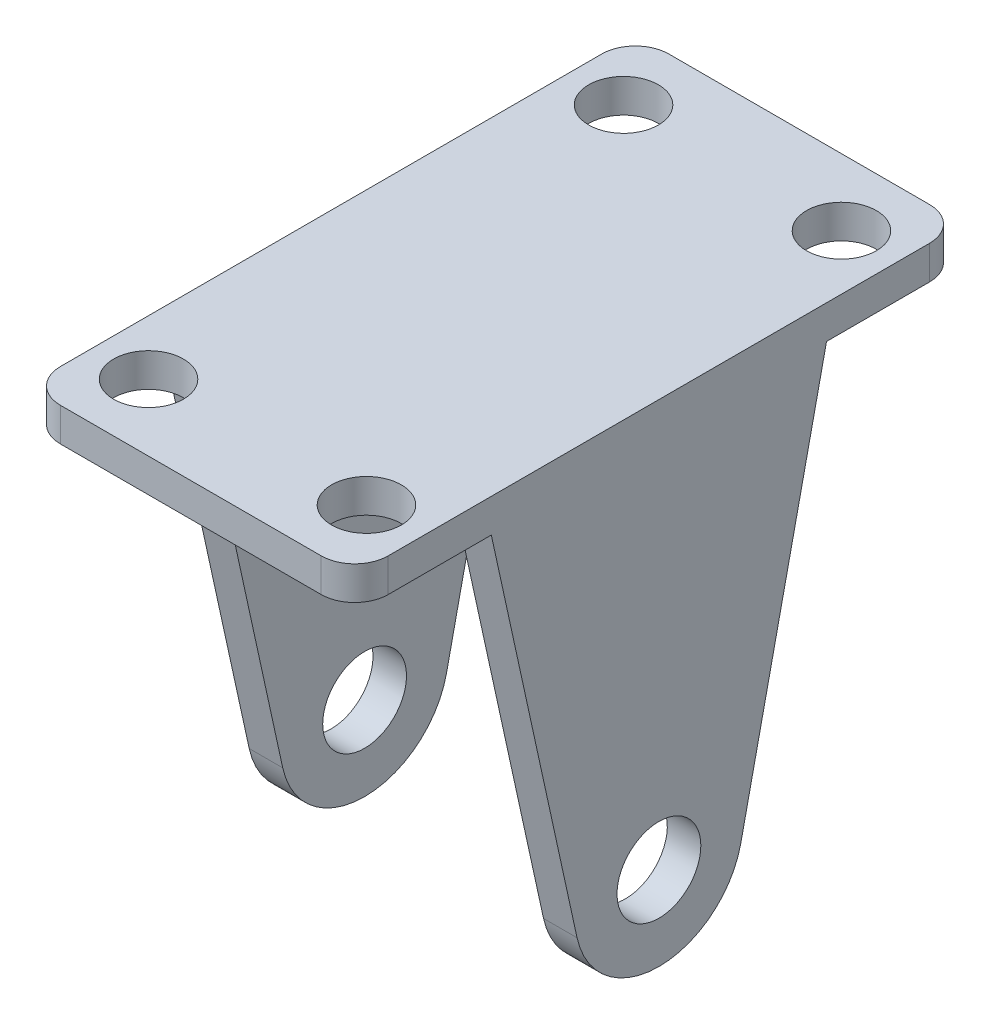
SolidWorks part; units mm, degrees
material "AISI 304"
ref_plane "Front Plane" through (0, 0, 0) normal (0, 0, 1) x (1, 0, 0)
ref_plane "Top Plane" through (0, 0, 0) normal (0, 1, 0) x (1, 0, 0)
ref_plane "Right Plane" through (0, 0, 0) normal (1, 0, 0) x (0, 0, -1)
sketch "Sketch1" plane through (0, 0, 0) normal (0, 1, 0) x (1, 0, 0)
  line L0 (0, 23.0505) -> (0, -23.0505) construction
  line L1 (12.4206, -23.0505) -> (-12.4206, -23.0505)
  line L2 (12.4206, -23.0505) -> (12.4206, 23.0505)
  line L3 (12.4206, 23.0505) -> (-12.4206, 23.0505)
  line L4 (-12.4206, -23.0505) -> (-12.4206, 23.0505)
  line L5 (12.4206, -23.0505) -> (-12.4206, 23.0505) construction
  line L6 (12.4206, 23.0505) -> (-12.4206, -23.0505) construction
  line L7 (-12.4206, 0) -> (12.4206, 0) construction
  circle A0 centre (-8.255, 17.9959) radius 2.6416
  circle A1 centre (8.255, 17.9959) radius 2.6416
  circle A2 centre (8.255, -17.9959) radius 2.6416
  circle A3 centre (-8.255, -17.9959) radius 2.6416
  point P0 (0, 0)
  dimension "D1" = 16.51
  dimension "D2" = 5.2832
  dimension "D3" = 35.9918
  dimension "D4" = 24.8412
  dimension "D5" = 46.101
extrude "Boss-Extrude1" add sketch "Sketch1" against normal blind 2.54 contours L2 L3 L4 L1
sketch "Sketch2" plane through (0, 0, 0) normal (1, 0, 0) x (0, 0, -1)
  line L0 (-6.2031, -32.2189) -> (-12.7, -2.54)
  line L1 (-23.0505, -2.54) -> (23.0505, -2.54) construction
  line L2 (-12.7, -2.54) -> (12.7, -2.54)
  line L3 (12.7, -2.54) -> (6.2031, -32.2189)
  line L5 (0, -2.54) -> (0, -30.861) construction
  line L6 (0, -30.861) -> (0, -50.8) construction
  line L7 (-23.0505, 0) -> (23.0505, 0) construction
  arc A0 (-6.2031, -32.2189) -> (6.2031, -32.2189) centre (0, -30.861) ccw
  arc A1 (6.2031, -32.2189) -> (0, -24.511) centre (0, -30.861) ccw construction
  arc A2 (0, -24.511) -> (-6.2031, -32.2189) centre (0, -30.861) ccw construction
  circle A3 centre (0, -30.861) radius 19.939 construction
  circle A4 centre (0, -30.861) radius 3.175
  dimension "D1" = 6.35
  dimension "D3" = 50.8
  dimension "D4" = 39.878
  dimension "D5" = 6.35
  dimension "D2" = 25.4
extrude "Boss-Extrude2" add sketch "Sketch2" along normal up to surface and the other way up to surface up to face at (12.4206, -1.27, 0) other way up to face at (-12.4206, -1.27, 0)
sketch "Sketch3" plane through (0, 0, 0) normal (0, 0, 1) x (1, 0, 0)
  line L0 (12.4206, -2.54) -> (-12.4206, -2.54) construction
  line L1 (-9.8806, -2.54) -> (9.8806, -2.54)
  line L2 (-9.8806, -2.54) -> (-9.8806, -37.211)
  line L3 (-9.8806, -37.211) -> (9.8806, -37.211)
  line L4 (9.8806, -2.54) -> (9.8806, -37.211)
  line L5 (-12.4206, -37.211) -> (12.4206, -37.211) construction
  line L6 (12.4206, -2.54) -> (12.4206, -32.2189) construction
  line L7 (-12.4206, -2.54) -> (-12.4206, -32.2189) construction
  dimension "D1" = 2.54
  dimension "D2" = 2.54
extrude "Cut-Extrude1" cut sketch "Sketch3" against normal through all and the other way through all
fillet "Fillet1" radius 2.54 6 edges at (-12.4206, -1.27, -23.0505) (12.4206, -1.27, -23.0505) (-12.4206, -1.27, 23.0505) (12.4206, -1.27, 23.0505) (-9.8806, -2.54, 0) (9.8806, -2.54, 0)
